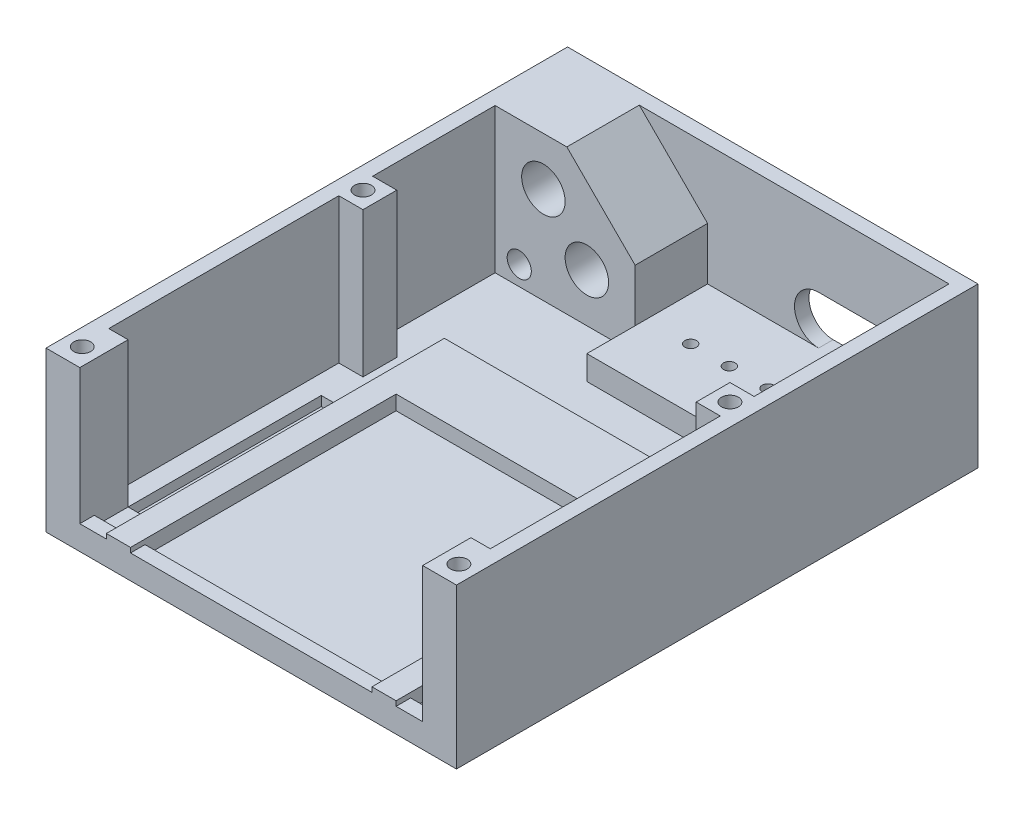
SolidWorks part; units mm, degrees
ref_plane "Front Plane" through (0, 0, 0) normal (0, 0, 1) x (1, 0, 0)
ref_plane "Top Plane" through (0, 0, 0) normal (0, 1, 0) x (1, 0, 0)
ref_plane "Right Plane" through (0, 0, 0) normal (1, 0, 0) x (0, 0, -1)
sketch "Sketch2" plane through (0, 0, 0) normal (0, 1, 0) x (1, 0, 0)
  line L1 (39.5, -52.5) -> (-39.5, -52.5)
  line L2 (39.5, -52.5) -> (39.5, 52.5)
  line L3 (39.5, 52.5) -> (-39.5, 52.5)
  line L4 (-39.5, -52.5) -> (-39.5, 52.5)
  line L5 (39.5, -52.5) -> (-39.5, 52.5) construction
  line L6 (39.5, 52.5) -> (-39.5, -52.5) construction
  point P0 (0, 0)
  dimension "D1" = 79
  dimension "D2" = 105
extrude "Boss-Extrude1" add sketch "Sketch2" along normal blind 3
sketch "Sketch9" plane through (0, 0, 0) normal (0, 1, 0) x (1, 0, 0)
  line L2 (-39.5, 52.5) -> (-39.5, -52.5)
  line L3 (-39.5, -52.5) -> (-42.5, -52.5)
  line L4 (-42.5, 52.5) -> (-42.5, -52.5)
  line L6 (39.5, 52.5) -> (39.5, -52.5)
  line L7 (39.5, -52.5) -> (42.5, -52.5)
  line L8 (42.5, 52.5) -> (42.5, -52.5)
  line L9 (39.5, 52.5) -> (-39.5, 52.5)
  line L10 (42.5, 52.5) -> (42.5, 55.5)
  line L11 (42.5, 55.5) -> (-42.5, 55.5)
  line L12 (-42.5, 52.5) -> (-42.5, 55.5)
  dimension "D1" = 3
  dimension "D2" = 3
  dimension "D3" = 3
sketch "Sketch3" plane through (0, 3, 0) normal (0, 1, 0) x (1, 0, 0)
  line L0 (0, -52.5) -> (0, 52.5) construction
  line L1 (-39.5, -52.5) -> (39.5, -52.5) construction
  line L2 (39.5, 52.5) -> (-39.5, 52.5) construction
  line L4 (30, -52.5) -> (-30, -52.5)
  line L5 (30, -52.5) -> (30, 17.5)
  line L6 (30, 17.5) -> (-30, 17.5)
  line L7 (-30, -52.5) -> (-30, 17.5)
  line L8 (30, -52.5) -> (-30, 17.5) construction
  line L9 (30, 17.5) -> (-30, -52.5) construction
  point P6 (0, -17.5)
  dimension "D1" = 60
  dimension "D2" = 70
extrude "support" add sketch "Sketch3" along normal blind 3
sketch "Sketch4" plane through (0, 6, 0) normal (0, 1, 0) x (1, 0, 0)
  line L0 (-30, -52.5) -> (30, -52.5) construction
  line L1 (-25, -52.5) -> (25, -52.5)
  line L2 (-25, -52.5) -> (-25, 2.5)
  line L3 (-25, 2.5) -> (25, 2.5)
  line L4 (25, -52.5) -> (25, 2.5)
  line L5 (30, 17.5) -> (-30, 17.5) construction
  line L6 (30, -52.5) -> (30, 17.5) construction
  line L7 (-30, 17.5) -> (-30, -52.5) construction
  dimension "D1" = 15
  dimension "D2" = 5
  dimension "D3" = 5
extrude "remove plastic" cut sketch "Sketch4" against normal blind 3
sketch "Sketch5" plane through (0, 3, 0) normal (0, 1, 0) x (1, 0, 0)
  line L0 (39.5, 52.5) -> (-39.5, 52.5) construction
  line L1 (-10.5, 52.5) -> (39.5, 52.5)
  line L2 (-10.5, 52.5) -> (-10.5, 27.5)
  line L3 (-10.5, 27.5) -> (39.5, 27.5)
  line L4 (39.5, 52.5) -> (39.5, 27.5)
  line L5 (39.5, -52.5) -> (39.5, 52.5) construction
  dimension "D1" = 50
  dimension "D2" = 25
extrude "Boss-Extrude3" add sketch "Sketch5" along normal blind 5
sketch "Sketch6" plane through (0, 8, 0) normal (0, 1, 0) x (1, 0, 0)
  line L0 (-10.5, 40) -> (39.5, 40) construction
  line L1 (-10.5, 52.5) -> (-10.5, 27.5) construction
  line L2 (39.5, 27.5) -> (39.5, 52.5) construction
  line L3 (14.5, 52.5) -> (14.5, 27.5) construction
  line L4 (39.5, 52.5) -> (-10.5, 52.5) construction
  line L5 (-10.5, 27.5) -> (39.5, 27.5) construction
  circle A0 centre (-1.5, 40) radius 1.2
  circle A1 centre (6.5, 40) radius 1.2
  circle A2 centre (14.5, 40) radius 1.2
  circle A3 centre (22.5, 40) radius 1.2
  circle A4 centre (30.5, 40) radius 1.2
  dimension "D1" = 2.4
  dimension "D2" = 8
  dimension "D3" = 8
  dimension "D4" = 8
  dimension "D5" = 8
extrude "Cut-Extrude2" cut sketch "Sketch6" against normal blind 5 draft 5
sketch "Sketch7" plane through (0, 3, 0) normal (0, 1, 0) x (1, 0, 0)
  line L0 (-39.5, 52.5) -> (-39.5, -52.5) construction
  line L1 (-10.5, 52.5) -> (-39.5, 52.5)
  line L2 (-10.5, 52.5) -> (-10.5, 37.5)
  line L3 (-10.5, 37.5) -> (-39.5, 37.5)
  line L4 (-39.5, 52.5) -> (-39.5, 37.5)
  dimension "D1" = 15
extrude "Boss-Extrude4" add sketch "Sketch7" along normal blind 30
extrude "Boss-Extrude5" add sketch "Sketch9" along normal up to surface (33 mm away) up to face at (-25, 33, -45)
sketch "Sketch8" plane through (0, 0, -37.5) normal (0, 0, 1) x (1, 0, 0)
  line L0 (-10.5, 33) -> (-10.5, 8) construction
  line L2 (-39.5, 33) -> (-10.5, 33) construction
  line L4 (-39.5, 3) -> (-10.5, 3) construction
  line L5 (-39.5, 33) -> (-39.5, 3) construction
  circle A0 centre (-20.5, 13) radius 4.5
  circle A1 centre (-34.5, 7) radius 2.5
  circle A2 centre (-29.5, 23) radius 4.5
  dimension "D1" = 9
  dimension "D2" = 5
  dimension "D3" = 10
  dimension "D8" = 10
  dimension "D4" = 10
  dimension "D5" = 10
  dimension "D6" = 5
  dimension "D7" = 4
extrude "Cut-Extrude3" cut sketch "Sketch8" against normal blind 31
sketch "Sketch10" plane through (0, 3, 0) normal (0, 1, 0) x (1, 0, 0)
  line L0 (0, -52.5) -> (0, 2.5) construction
  line L1 (-25, -52.5) -> (25, -52.5) construction
  line L2 (25, 2.5) -> (-25, 2.5) construction
  line L3 (-35.5, -52.5) -> (35.5, -52.5) construction
  line L4 (39.5, -52.5) -> (39.5, 27.5) construction
  line L5 (-39.5, -52.5) -> (-35.5, -52.5)
  line L6 (-39.5, -52.5) -> (-39.5, -42.5)
  line L7 (-39.5, -42.5) -> (-35.5, -42.5)
  line L8 (-35.5, -52.5) -> (-35.5, -42.5)
  line L9 (35.5, -52.5) -> (39.5, -52.5)
  line L10 (35.5, -52.5) -> (35.5, -42.5)
  line L11 (35.5, -42.5) -> (39.5, -42.5)
  line L12 (39.5, -52.5) -> (39.5, -42.5)
  dimension "D1" = 71
  dimension "D2" = 10
  dimension "D3" = 10
extrude "Boss-Extrude6" add sketch "Sketch10" along normal up to surface (30 mm away) up to face at (-2.1, 33, -8.1)
sketch "Sketch11" plane through (0, 0, -52.5) normal (0, 0, 1) x (1, 0, 0)
  line L0 (12.5, 18) -> (32.5, 18)
  line L1 (39.5, 33) -> (39.5, 8) construction
  line L2 (12.5, 8) -> (32.5, 8)
  line L5 (39.5, 8) -> (-10.5, 8) construction
  arc A0 (12.5, 18) -> (12.5, 8) centre (12.5, 13) ccw
  arc A1 (32.5, 8) -> (32.5, 18) centre (32.5, 13) ccw
  dimension "D1" = 7
  dimension "D2" = 10
  dimension "D3" = 10
  dimension "D4" = 20
extrude "Cut-Extrude4" cut sketch "Sketch11" against normal up to surface (3 mm away) up to face at (-25, 23, -55.5)
sketch "Sketch12" plane through (0, 0, -37.5) normal (0, 0, 1) x (1, 0, 0)
  line L0 (-24.6421, 33) -> (-10.5, 18.8579)
  line L1 (-39.5, 33) -> (-10.5, 33) construction
  line L2 (-10.5, 33) -> (-10.5, 8) construction
  line L3 (-10.5, 18.8579) -> (-10.5, 33)
  line L4 (-10.5, 33) -> (-24.6421, 33)
  dimension "D1" = 45
  dimension "D2" = 20
extrude "Cut-Extrude5" cut sketch "Sketch12" against normal up to surface (15 mm away) up to face at (18.5, 16.75, -52.5)
sketch "Sketch13" plane through (0, 3, 0) normal (0, 1, 0) x (1, 0, 0)
  line L0 (-39.5, 37.5) -> (-39.5, -42.5) construction
  line L1 (-39.5, 5.1381) -> (-34.5, 5.1381)
  line L2 (-39.5, 5.1381) -> (-39.5, 12.1381)
  line L3 (-39.5, 12.1381) -> (-34.5, 12.1381)
  line L4 (-34.5, 5.1381) -> (-34.5, 12.1381)
  line L5 (39.5, -42.5) -> (39.5, 27.5) construction
  line L6 (39.5, 12.1381) -> (34.5, 12.1381)
  line L7 (39.5, 12.1381) -> (39.5, 5.1381)
  line L8 (39.5, 5.1381) -> (34.5, 5.1381)
  line L9 (34.5, 12.1381) -> (34.5, 5.1381)
  dimension "D1" = 5
  dimension "D2" = 7
  dimension "D3" = 7
  dimension "D4" = 7
  dimension "D5" = 5
  dimension "D6" = 7
extrude "Boss-Extrude7" add sketch "Sketch13" along normal up to surface (30 mm away) up to face at (-3.5203, 33, 6.3571)
sketch "Sketch14" plane through (0, 33, 0) normal (0, 1, 0) x (1, 0, 0)
  line L0 (-35.5, -52.5) -> (-42.5, -52.5) construction
  line L1 (-42.5, -52.5) -> (-42.5, 55.5) construction
  line L2 (42.5, -52.5) -> (35.5, -52.5) construction
  line L3 (42.5, 55.5) -> (42.5, -52.5) construction
  line L4 (39.5, 5.1381) -> (34.5, 5.1381) construction
  line L5 (-34.5, 5.1381) -> (-39.5, 5.1381) construction
  circle A0 centre (-39, -48.5) radius 1.75
  circle A1 centre (39, -48.5) radius 1.75
  circle A2 centre (38, 8.6381) radius 1.75
  circle A3 centre (-38, 8.6381) radius 1.75
  dimension "D1" = 3.5
  dimension "D2" = 4
  dimension "D3" = 3.5
  dimension "D4" = 4
  dimension "D5" = 3.5
  dimension "D6" = 4.5
  dimension "D7" = 3.5
  dimension "D8" = 4.5
  dimension "D9" = 3.5
extrude "Cut-Extrude6" cut sketch "Sketch14" against normal blind 20 draft 2
sketch "Sketch16" plane through (0, 3, 0) normal (0, 1, 0) x (1, 0, 0)
  line L0 (-30, 17.5) -> (-30, -52.5) construction
  line L1 (-35.5, -42.5) -> (-30, -42.5)
  line L2 (-35.5, -42.5) -> (-35.5, -2.5)
  line L3 (-35.5, -2.5) -> (-30, -2.5)
  line L4 (-30, -42.5) -> (-30, -2.5)
  line L5 (30, -52.5) -> (30, 17.5) construction
  line L6 (35.5, -42.5) -> (30, -42.5)
  line L7 (35.5, -42.5) -> (35.5, -2.5)
  line L8 (35.5, -2.5) -> (30, -2.5)
  line L9 (30, -42.5) -> (30, -2.5)
  dimension "D1" = 20
  dimension "D2" = 20
extrude "Sliders" cut sketch "Sketch16" against normal blind 2
sketch "Sketch17" plane through (0, 0, 52.5) normal (0, 0, 1) x (1, 0, 0)
  line L0 (35.5, 33) -> (35.5, 3) construction
  line L1 (-35.5, 3) -> (35.5, 3)
  line L2 (-35.5, 3) -> (-35.5, 5)
  line L3 (-35.5, 5) -> (35.5, 5)
  line L4 (35.5, 3) -> (35.5, 5)
  dimension "D1" = 2
extrude "Boss-Extrude9" add sketch "Sketch17" against normal blind 3
equation "\"c_outside_width\" = 75mm"
equation "\"c_total_length\" = 80mm"
equation "\"c_inside_width\"= 70mm"
equation "\"wall_thickness\" = 3mm"
equation "\"D1@Sketch2\"=\"c_outside_width\" + \"wall_thickness\" + 1"
equation "\"D1@Boss-Extrude1\"=\"wall_thickness\""
equation "\"c_bottom_support_width\"=60"
equation "\"D1@Sketch3\"=\"c_bottom_support_width\""
equation "\"c_bottom_support_length\"=70"
equation "\"D2@Sketch3\"=\"c_bottom_support_length\""
equation "\"c_bottom_support_height\"= 3mm"
equation "\"D1@support\"=\"c_bottom_support_height\""
equation "\"D1@remove plastic\"=\"c_bottom_support_height\""
equation "\"D1@Sketch9\"=\"wall_thickness\""
equation "\"D2@Sketch9\"=\"wall_thickness\""
equation "\"D3@Sketch9\"=\"wall_thickness\""
equation "\"c__outside_height\"= 34.5mm"
equation "\"c_inside_height\"= 30mm"
equation "\"D1@Boss-Extrude5\"=\"c__outside_height\""
equation "\"D1@Sketch10\"=\"c_inside_width\"+1"
equation "\"case_screw_diameter\"=3.5"
equation "\"D1@Sketch14\"=\"case_screw_diameter\""
equation "\"D1@Boss-Extrude4\" = \"c_inside_height\""
